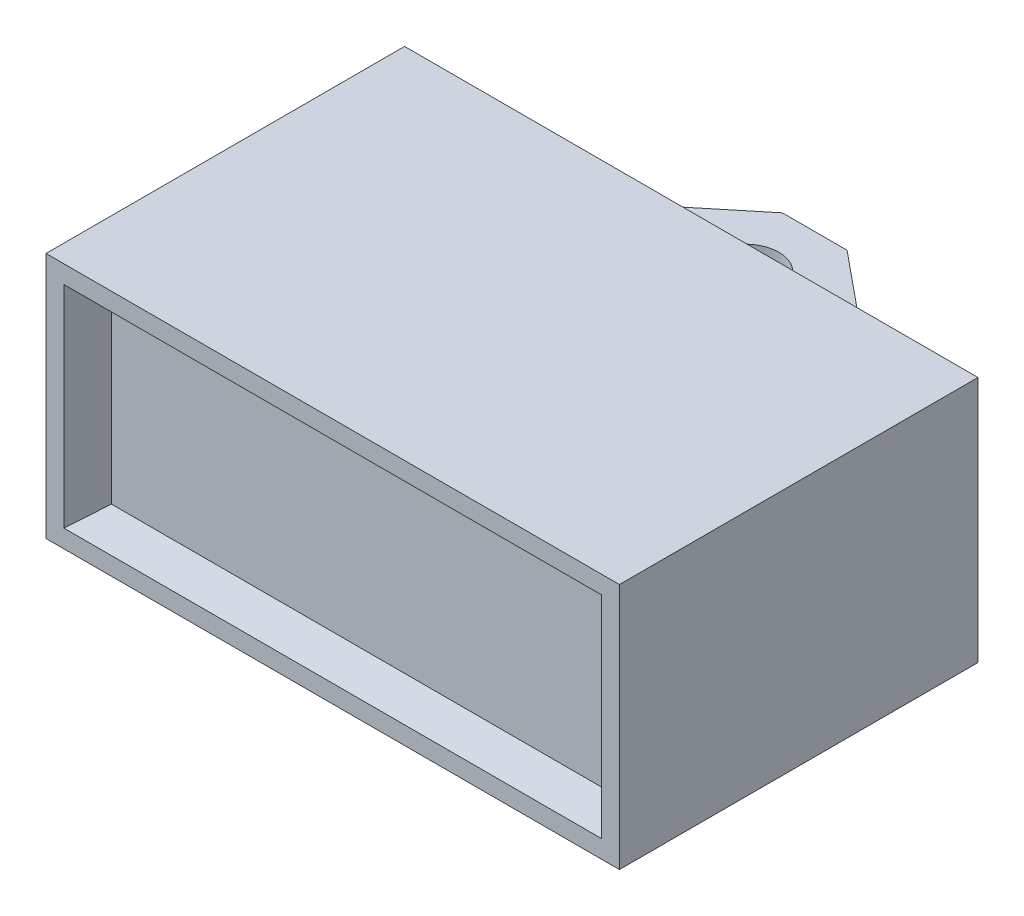
SolidWorks part; units mm, degrees
ref_plane "Front Plane" through (0, 0, 0) normal (0, 0, 1) x (1, 0, 0)
ref_plane "Top Plane" through (0, 0, 0) normal (0, 1, 0) x (1, 0, 0)
ref_plane "Right Plane" through (0, 0, 0) normal (1, 0, 0) x (0, 0, -1)
sketch "Sketch1" plane through (0, 0, 0) normal (0, 0, 1) x (1, 0, 0)
  line L1 (553.1032, 1190.3934) -> (715.6759, 1190.3934)
  line L2 (553.1032, 1190.3934) -> (553.1032, 1260.3831)
  line L3 (553.1032, 1260.3831) -> (715.6759, 1260.3831)
  line L4 (715.6759, 1190.3934) -> (715.6759, 1260.3831)
  dimension "D1" = 69.9897
  dimension "D2" = 162.5727
extrude "Boss-Extrude1" add sketch "Sketch1" along normal blind 101.6635
sketch "Sketch2" plane through (0, 1260.3831, 0) normal (0, 1, 0) x (1, 0, 0)
  line L0 (582.5672, 0) -> (625.2138, 34.9885)
  line L1 (715.6759, 0) -> (553.1032, 0) construction
  line L2 (625.2138, 34.9885) -> (643.5653, 34.9885)
  line L3 (634.3895, 34.9885) -> (634.3895, 0) construction
  line L5 (643.5653, 34.9885) -> (686.2119, 0)
  line L6 (715.6759, -101.6635) -> (715.6759, 0) construction
  line L7 (582.5672, 0) -> (686.2119, 0)
  circle A0 centre (634.3895, 15.3035) radius 9.525
  point P5 (634.3895, 34.9885)
  dimension "D4" = 19.05
  dimension "D1" = 18.3515
  dimension "D2" = 34.9885
  dimension "D3" = 29.464
  dimension "D5" = 19.685
extrude "Boss-Extrude2" add sketch "Sketch2" against normal through all
sketch "Sketch3" plane through (553.1032, 0, 0) normal (-1, 0, 0) x (0, 0, 1)
  line L0 (0, 1190.3934) -> (0, 1260.3831) construction
  line L1 (-34.9885, 1190.3934) -> (0, 1190.3934)
  line L2 (-34.9885, 1190.3934) -> (-34.9885, 1212.6883)
  line L3 (-34.9885, 1212.6883) -> (0, 1212.6883)
  line L4 (0, 1190.3934) -> (0, 1212.6883)
  line L5 (0, 1260.3831) -> (0, 1190.3934) construction
  line L6 (-34.9885, 1260.3831) -> (0, 1260.3831)
  line L7 (-34.9885, 1260.3831) -> (-34.9885, 1238.0883)
  line L8 (-34.9885, 1238.0883) -> (0, 1238.0883)
  line L9 (0, 1260.3831) -> (0, 1238.0883)
  line L10 (-17.4942, 1238.0883) -> (-17.4942, 1212.6883) construction
  line L11 (0, 1225.3883) -> (-17.4942, 1225.3883) construction
  dimension "D1" = 25.4
extrude "Cut-Extrude1" cut sketch "Sketch3" against normal through all
ref_plane "Plane1" through (0, 1225.3883, 0) normal (0, 1, 0) x (1, 0, 0)
ref_plane "Plane2" through (634.3895, 0, 0) normal (-1, 0, 0) x (0, 0, 1)
sketch "Sketch5" plane through (0, 1225.3883, 0) normal (0, 1, 0) x (1, 0, 0)
  line L0 (558.1832, -101.6635) -> (561.4852, -91.5035)
  line L1 (715.6759, -101.6635) -> (553.1032, -101.6635) construction
  line L2 (561.4852, -91.5035) -> (707.2939, -91.5035)
  line L3 (707.2939, -91.5035) -> (710.5959, -101.6635)
  line L4 (634.3895, -91.5035) -> (634.3895, -101.6635) construction
  line L5 (558.1832, -101.6635) -> (710.5959, -101.6635)
  line L6 (553.1032, -101.6635) -> (553.1032, 0) construction
  dimension "D1" = 8.382
  dimension "D2" = 5.08
  dimension "D3" = 10.16
extrude "Cut-Extrude2" cut sketch "Sketch5" against normal mid plane 54.864
sketch "Sketch6" plane through (634.3895, 0, 0) normal (-1, 0, 0) x (0, 0, 1)
  line L0 (101.6635, 1255.3031) -> (91.5035, 1252.8203)
  line L1 (101.6635, 1260.3831) -> (101.6635, 1190.3934) construction
  line L3 (91.5035, 1197.9563) -> (101.6635, 1195.4734)
  line L5 (91.5035, 1225.3883) -> (101.6635, 1225.3883) construction
  line L6 (101.6635, 1260.3831) -> (0, 1260.3831) construction
  line L11 (91.5035, 1252.8203) -> (91.5035, 1197.9563) construction
  line L12 (91.5035, 1252.8203) -> (101.6635, 1252.8203) construction
  line L13 (91.5035, 1252.8203) -> (101.6635, 1252.8203)
  line L14 (101.6635, 1252.8203) -> (101.6635, 1255.3031)
  line L15 (91.5035, 1197.9563) -> (101.6635, 1197.9563)
  line L16 (101.6635, 1197.9563) -> (101.6635, 1195.4734)
  point P14 (91.5035, 1225.3883)
  point P16 (101.6635, 1225.3883)
  dimension "D1" = 5.08
  dimension "D2" = 10.16
extrude "Cut-Extrude3" cut sketch "Sketch6" against normal up to surface (72.9043 mm away)
sketch "Sketch8" plane through (634.3895, 0, 0) normal (1, 0, 0) x (0, 0, -1)
  line L0 (-101.6635, 1255.3031) -> (-91.5035, 1252.8203)
  line L1 (-91.5035, 1252.8203) -> (-91.5035, 1197.9563)
  line L2 (-91.5035, 1197.9563) -> (-101.6635, 1195.4734)
  line L3 (-101.6635, 1195.4734) -> (-101.6635, 1255.3031)
extrude "Cut-Extrude5" cut sketch "Sketch8" against normal up to surface (76.2063 mm away)
